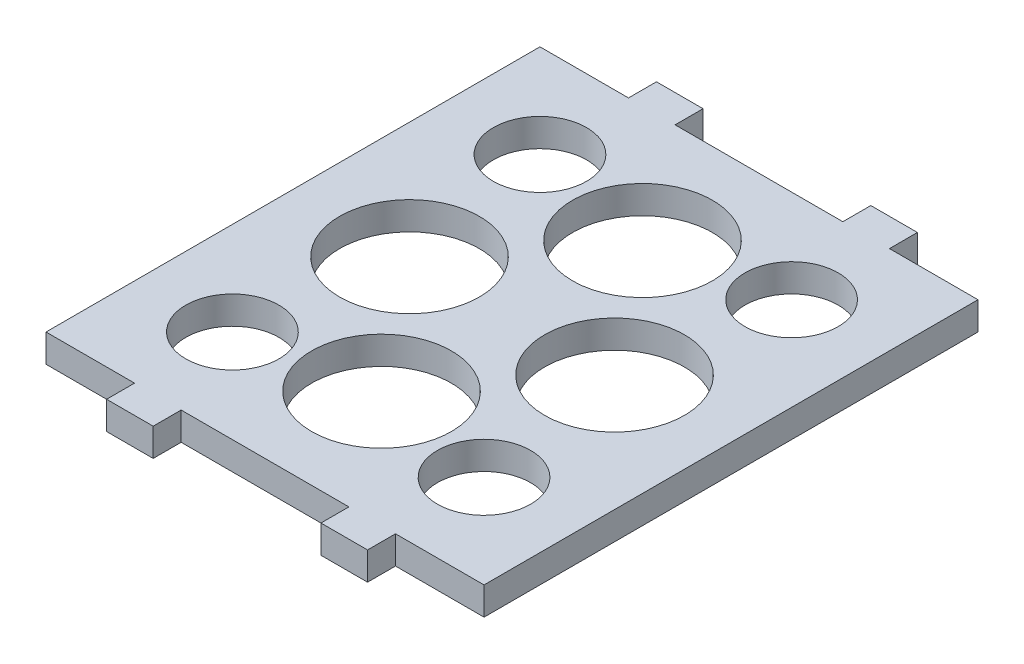
SolidWorks part; units mm, degrees
ref_plane "Front Plane" through (0, 0, 0) normal (0, 0, 1) x (1, 0, 0)
ref_plane "Top Plane" through (0, 0, 0) normal (0, 1, 0) x (1, 0, 0)
ref_plane "Right Plane" through (0, 0, 0) normal (1, 0, 0) x (0, 0, -1)
sketch "Sketch1" plane through (0, 0, 0) normal (0, 1, 0) x (1, 0, 0)
  line L0 (19, 0) -> (29, 0) construction
  line L1 (0, 0) -> (19, 0)
  line L2 (0, 0) -> (0, 106)
  line L3 (0, 53) -> (94, 53) construction
  line L4 (94, 0) -> (94, 106)
  line L5 (-6, 53) -> (100, 53) construction
  line L6 (-6, 112) -> (-6, -6) construction
  line L7 (-6, -6) -> (100, -6) construction
  line L8 (100, 112) -> (100, -6) construction
  line L9 (75, 0) -> (94, 0)
  line L10 (65, 0) -> (75, 0) construction
  line L11 (29, 0) -> (65, 0)
  line L12 (19, 0) -> (19, -6)
  line L13 (19, -6) -> (29, -6)
  line L14 (29, -6) -> (29, 0)
  line L15 (65, 0) -> (65, -6)
  line L16 (65, -6) -> (75, -6)
  line L17 (75, -6) -> (75, 0)
  line L18 (65, 106) -> (75, 106) construction
  line L19 (-6, 112) -> (100, 112) construction
  line L20 (19, 106) -> (29, 106) construction
  line L21 (75, 112) -> (75, 106)
  line L22 (65, 112) -> (75, 112)
  line L23 (65, 106) -> (65, 112)
  line L24 (29, 112) -> (29, 106)
  line L25 (19, 112) -> (29, 112)
  line L26 (19, 106) -> (19, 112)
  line L27 (29, 106) -> (65, 106)
  line L28 (75, 106) -> (94, 106)
  line L29 (0, 106) -> (19, 106)
  line L30 (47, 106) -> (47, 0) construction
  line L31 (94, 96) -> (0, 96) construction
  line L32 (10, 106) -> (10, 0) construction
  line L33 (84, 106) -> (84, 0) construction
  line L34 (0, 10) -> (94, 10) construction
  circle A0 centre (25, 53) radius 15
  circle A1 centre (69, 53) radius 15
  circle A2 centre (47, 81) radius 15
  circle A3 centre (47, 25) radius 15
  circle A4 centre (20, 20) radius 10
  circle A5 centre (20, 86) radius 10
  circle A6 centre (74, 86) radius 10
  circle A7 centre (74, 20) radius 10
  dimension "D3" = 25
  dimension "D9" = 25
  dimension "D10" = 30
  dimension "D11" = 25
  dimension "D12" = 25
  dimension "D13" = 20
  dimension "D1" = 53
  dimension "D2" = 94
  dimension "D4" = 6
  dimension "D5" = 6
  dimension "D6" = 6
  dimension "D7" = 25
  dimension "D8" = 10
extrude "Boss-Extrude1" add sketch "Sketch1" along normal blind 6
